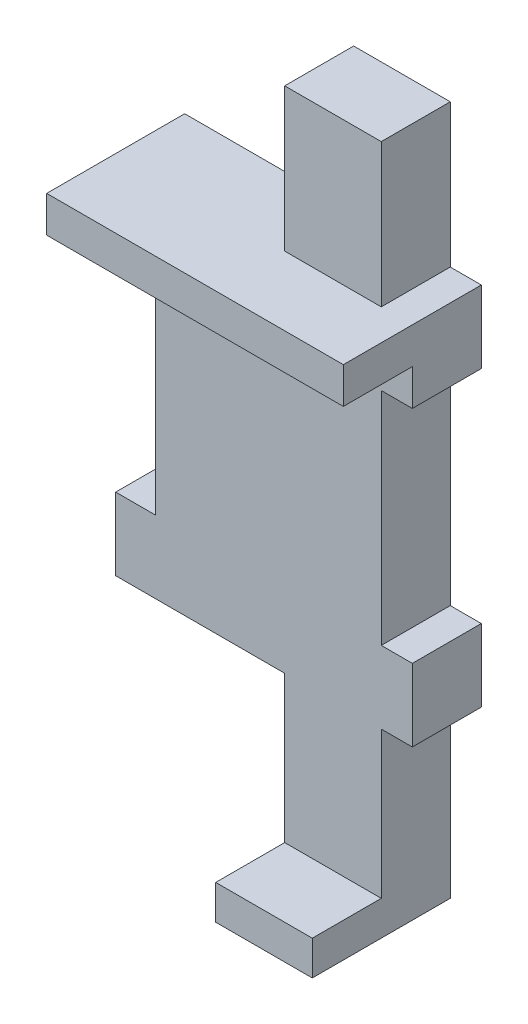
SolidWorks part; units mm, degrees
ref_plane "Front Plane" through (0, 0, 0) normal (0, 0, 1) x (1, 0, 0)
ref_plane "Top Plane" through (0, 0, 0) normal (0, 1, 0) x (1, 0, 0)
ref_plane "Right Plane" through (0, 0, 0) normal (1, 0, 0) x (0, 0, -1)
sketch "Sketch1" plane through (0, 0, 0) normal (0, 0, 1) x (1, 0, 0)
  line L1 (-2.8, -20) -> (2.8, -20)
  line L2 (-2.8, -20) -> (-2.8, 20)
  line L3 (-2.8, 20) -> (2.8, 20)
  line L4 (2.8, -20) -> (2.8, 20)
  line L5 (-2.8, -20) -> (2.8, 20) construction
  line L6 (-2.8, 20) -> (2.8, -20) construction
  point P0 (0, 0)
  dimension "D1" = 40
  dimension "D2" = 5.6
extrude "Boss-Extrude1" add sketch "Sketch1" along normal blind 4 contours L4 L3 L2 L1
sketch "Sketch2" plane through (0, 0, 4) normal (0, 0, 1) x (1, 0, 0)
  line L0 (2.8, -20) -> (2.8, 20) construction
  line L1 (-2.8, -20) -> (2.8, -20)
  line L2 (-2.8, -20) -> (-2.8, -18)
  line L3 (-2.8, -18) -> (2.8, -18)
  line L4 (2.8, -20) -> (2.8, -18)
  dimension "D1" = 2
extrude "Boss-Extrude2" add sketch "Sketch2" along normal blind 4
sketch "Sketch4" plane through (-2.8, 0, 0) normal (-1, 0, 0) x (0, 0, 1)
  line L0 (0, -20) -> (0, 20) construction
  line L1 (0, 11.7) -> (4, 11.7)
  line L2 (0, 11.7) -> (0, 7.5)
  line L3 (0, 7.5) -> (4, 7.5)
  line L4 (4, 11.7) -> (4, 7.5)
  line L5 (4, -18) -> (4, 20) construction
  line L6 (8, -20) -> (0, -20) construction
  dimension "D1" = 4.2
  dimension "D2" = 27.5
extrude "Boss-Extrude3" add sketch "Sketch4" along normal blind 1.8
ref_plane "Plane1" through (0, 0, 0) normal (-1, 0, 0) x (0, 0, 1)
mirror "Mirror1" about plane through (0, 0, 0) normal (-1, 0, 0) of "Boss-Extrude3"
sketch "Sketch6" plane through (0, 0, 4) normal (0, 0, 1) x (1, 0, 0)
  line L0 (2.8, 1.1) -> (-2.8, 1.1) construction
  line L1 (2.8, -18) -> (2.8, 7.5) construction
  line L2 (-2.8, -18) -> (-2.8, 7.5) construction
  line L3 (2.8, -18) -> (-2.8, -18) construction
  line L4 (4.6, 7.5) -> (2.8, 7.5) construction
  dimension "D1" = 19.1
  dimension "D2" = 6.4
sketch "Sketch7" plane through (-2.8, 0, 0) normal (-1, 0, 0) x (0, 0, 1)
  line L0 (4, 1.1) -> (0, 1.1) construction
  line L1 (4, -18) -> (4, 7.5) construction
  line L2 (0, -20) -> (0, 7.5) construction
  line L3 (8, -18) -> (4, -18) construction
  dimension "D1" = 19.1
ref_plane "Plane3" through (0, 1.1, 0) normal (0, -1, 0) x (-1, 0, 0)
mirror "Mirror2" about plane through (0, 1.1, 0) normal (0, -1, 0) of "Mirror1", "Boss-Extrude3"
sketch "Sketch8" plane through (-4.6, 0, 0) normal (-1, 0, 0) x (0, 0, 1)
  line L1 (0, 11.7) -> (4, 11.7)
  line L2 (0, 11.7) -> (0, 7.5)
  line L3 (0, 7.5) -> (4, 7.5)
  line L4 (4, 11.7) -> (4, 7.5)
  line L5 (0, -5.3) -> (4, -5.3)
  line L6 (0, -5.3) -> (0, -9.5)
  line L7 (0, -9.5) -> (4, -9.5)
  line L8 (4, -5.3) -> (4, -9.5)
extrude "Boss-Extrude4" add sketch "Sketch8" along normal blind 8
sketch "Sketch9" plane through (0, 0, 4) normal (0, 0, 1) x (1, 0, 0)
  line L0 (4.6, 7.5) -> (4.6, 11.7) construction
  line L1 (-12.6, 11.7) -> (4.6, 11.7)
  line L2 (-12.6, 11.7) -> (-12.6, 9.6)
  line L3 (-12.6, 9.6) -> (4.6, 9.6)
  line L4 (4.6, 11.7) -> (4.6, 9.6)
extrude "Boss-Extrude5" add sketch "Sketch9" along normal blind 4
sketch "Sketch10" plane through (-2.8, 0, 0) normal (-1, 0, 0) x (0, 0, 1)
  line L1 (0, 7.5) -> (4, 7.5)
  line L2 (0, 7.5) -> (0, -5.3)
  line L3 (0, -5.3) -> (4, -5.3)
  line L4 (4, 7.5) -> (4, -5.3)
extrude "Boss-Extrude6" add sketch "Sketch10" along normal blind 7.5
sketch "Sketch11" plane through (0, 0, 0) normal (0, 0, -1) x (-1, 0, 0)
  line L1 (2.8, -20) -> (-2.8, -20) construction
  line L2 (-2.8, -5.3) -> (-2.8, 7.5) construction
  circle A0 centre (4.9, 1.1) radius 1.5
  point P2 (0, 0)
  dimension "D1" = 3
  dimension "D2" = 7.7
  dimension "D3" = 21.1
extrude "Cut-Extrude1" cut sketch "Sketch11" against normal blind 1
